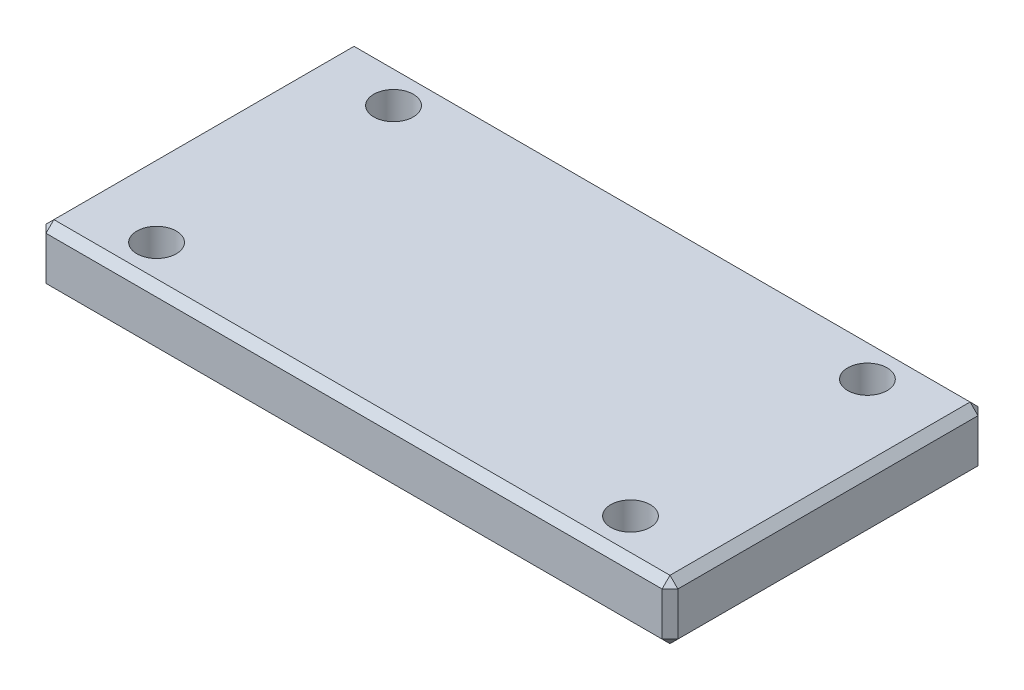
SolidWorks part; units mm, degrees
ref_plane "Front Plane" through (0, 0, 0) normal (0, 0, 1) x (1, 0, 0)
ref_plane "Top Plane" through (0, 0, 0) normal (0, 1, 0) x (1, 0, 0)
ref_plane "Right Plane" through (0, 0, 0) normal (1, 0, 0) x (0, 0, -1)
sketch "Sketch1" plane through (0, 0, 0) normal (0, 1, 0) x (1, 0, 0)
  line L1 (50.8, -25.4) -> (-50.8, -25.4)
  line L2 (50.8, -25.4) -> (50.8, 25.4)
  line L3 (50.8, 25.4) -> (-50.8, 25.4)
  line L4 (-50.8, -25.4) -> (-50.8, 25.4)
  line L5 (50.8, -25.4) -> (-50.8, 25.4) construction
  line L6 (50.8, 25.4) -> (-50.8, -25.4) construction
  point P0 (0, 0)
  dimension "D1" = 50.8
  dimension "D2" = 101.6
extrude "Boss-Extrude1" add sketch "Sketch1" along normal blind 9.525
chamfer "Chamfer1" distance 1.27 angle 45 12 edges at (0, 0, 25.4) (50.8, 0, 0) (0, 0, -25.4) (-50.8, 0, 0) (0, 9.525, -25.4) (50.8, 4.7625, -25.4) (50.8, 9.525, 0) (-50.8, 4.7625, -25.4) (-50.8, 9.525, 0) (-50.8, 4.7625, 25.4) (0, 9.525, 25.4) (50.8, 4.7625, 25.4)
sketch "Sketch2" plane through (0, 9.525, 0) normal (0, 1, 0) x (1, 0, 0)
  line L0 (0, 25.4) -> (0, 0) construction
  line L1 (-49.53, 25.4) -> (49.53, 25.4) construction
  line L2 (0, 0) -> (-50.8, 0) construction
  line L3 (-50.8, -24.13) -> (-50.8, 24.13) construction
  circle A0 centre (-38.1, 19.05) radius 3.175
  circle A1 centre (-38.1, -19.05) radius 3.175
  circle A2 centre (38.1, -19.05) radius 3.175
  circle A3 centre (38.1, 19.05) radius 3.175
  dimension "D3" = 6.35
  dimension "D1" = 6.35
  dimension "D2" = 12.7
extrude "Cut-Extrude1" cut sketch "Sketch2" against normal through all
